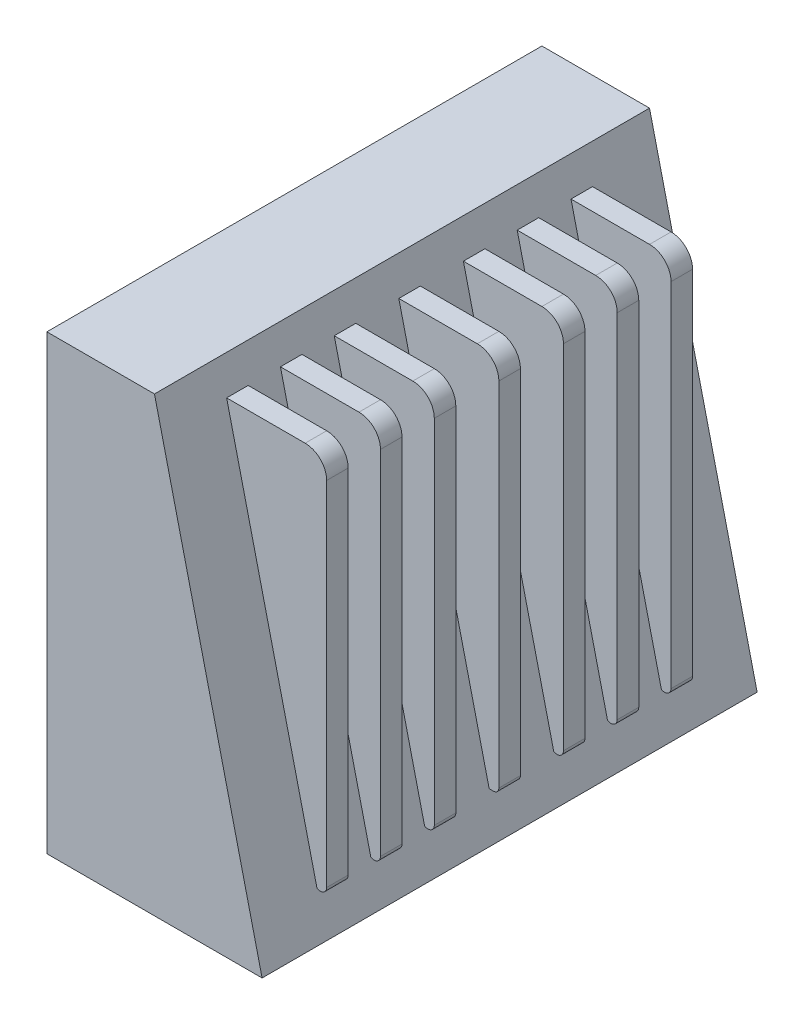
SolidWorks part; units mm, degrees
ref_plane "Alzado" through (0, 0, 0) normal (0, 0, 1) x (1, 0, 0)
ref_plane "Planta" through (0, 0, 0) normal (0, 1, 0) x (1, 0, 0)
ref_plane "Vista lateral" through (0, 0, 0) normal (1, 0, 0) x (0, 0, -1)
sketch "Croquis1" plane through (0, 0, 0) normal (0, 1, 0) x (1, 0, 0)
  line L1 (-10, -23) -> (10, -23)
  line L2 (-10, -23) -> (-10, 23)
  line L3 (-10, 23) -> (10, 23)
  line L4 (10, -23) -> (10, 23)
  line L5 (-10, -23) -> (10, 23) construction
  line L6 (-10, 23) -> (10, -23) construction
  point P0 (0, 0)
  dimension "D1" = 20
  dimension "D2" = 46
extrude "Saliente-Extruir1" add sketch "Croquis1" along normal blind 42
sketch "Croquis2" plane through (0, 0, 23) normal (0, 0, 1) x (1, 0, 0)
  line L0 (10, 0) -> (-0.1917, 42.8034)
  line L2 (-0.1917, 42.8034) -> (10, 42)
  line L3 (10, 42) -> (10, 0)
  dimension "D1" = 44
extrude "Cortar-Extruir1" cut sketch "Croquis2" against normal through all
sketch "Croquis3" plane through (0, 0, 0) normal (0, 0, 1) x (1, 0, 0)
  line L0 (10, 0) -> (10, 42) construction
  line L1 (-0.0004, 42) -> (10, 42) construction
  line L2 (9.0991, 3.7838) -> (9.5, 3.7838)
  line L3 (-0.0004, 42) -> (10, 0) construction
  line L4 (10, 4.2838) -> (10, 37.0371)
  line L5 (8, 39.0371) -> (0.7051, 39.0371)
  line L6 (0.7051, 39.0371) -> (9.0991, 3.7838)
  arc A0 (10, 37.0371) -> (8, 39.0371) centre (8, 37.0371) ccw
  arc A1 (9.5, 3.7838) -> (10, 4.2838) centre (9.5, 4.2838) ccw
  point P13 (10, 39.0371)
  point P16 (10, 3.7838)
  dimension "D1" = 2
  dimension "D2" = 0.5
extrude "Saliente-Extruir4" add sketch "Croquis3" along normal mid plane 2
ref_plane "Plano13" through (0, 0, 6) normal (0, 0, 1) x (1, 0, 0)
ref_plane "Plano14" through (0, 0, 11) normal (0, 0, 1) x (1, 0, 0)
ref_plane "Plano15" through (0, 0, 16) normal (0, 0, 1) x (1, 0, 0)
ref_plane "Plano16" through (0, 0, -6) normal (0, 0, -1) x (-1, 0, 0)
ref_plane "Plano17" through (0, 0, -11) normal (0, 0, -1) x (-1, 0, 0)
ref_plane "Plano18" through (0, 0, -16) normal (0, 0, -1) x (-1, 0, 0)
sketch "Croquis5" plane through (0, 0, 6) normal (0, 0, 1) x (1, 0, 0)
  line L0 (0.7051, 39.0371) -> (8, 39.0371)
  line L1 (10, 37.0371) -> (10, 4.2838)
  line L2 (9.0991, 3.7838) -> (0.7051, 39.0371)
  arc A0 (8, 39.0371) -> (10, 37.0371) centre (8, 37.0371) cw
  arc A1 (10, 37.0371) -> (8, 39.0371) centre (8, 37.0371) ccw construction
  arc A2 (10, 4.2838) -> (9.0991, 3.7838) centre (9.4108, 4.2838) cw
extrude "Saliente-Extruir5" add sketch "Croquis5" along normal mid plane 2
sketch "Croquis6" plane through (0, 0, 11) normal (0, 0, 1) x (1, 0, 0)
  line L0 (0.7051, 39.0371) -> (8, 39.0371)
  line L1 (10, 37.0371) -> (10, 4.2838)
  line L2 (9.0991, 3.7838) -> (0.7051, 39.0371)
  line L3 (8, 39.0371) -> (0.7051, 39.0371) construction
  line L4 (0.7051, 39.0371) -> (9.0991, 3.7838) construction
  line L5 (10, 4.2838) -> (10, 37.0371) construction
  arc A0 (8, 39.0371) -> (10, 37.0371) centre (8, 37.0371) cw
  arc A1 (10, 4.2838) -> (9.0991, 3.7838) centre (9.4108, 4.2838) cw
  arc A2 (9.0991, 3.7838) -> (10, 4.2838) centre (9.4108, 4.2838) ccw construction
extrude "Saliente-Extruir6" add sketch "Croquis6" along normal mid plane 2
sketch "Croquis7" plane through (0, 0, 16) normal (0, 0, 1) x (1, 0, 0)
  line L0 (0.7051, 39.0371) -> (8, 39.0371)
  line L1 (10, 37.0371) -> (10, 4.2838)
  line L2 (8.9072, 4.5896) -> (0.7051, 39.0371)
  line L3 (8, 39.0371) -> (0.7051, 39.0371) construction
  line L4 (0.7051, 39.0371) -> (9.0991, 3.7838) construction
  line L5 (10, 4.2838) -> (10, 37.0371) construction
  arc A0 (8, 39.0371) -> (10, 37.0371) centre (8, 37.0371) cw
  arc A1 (10, 4.2838) -> (8.9072, 4.5896) centre (9.4108, 4.2838) cw
  arc A2 (9.0991, 3.7838) -> (10, 4.2838) centre (9.4108, 4.2838) ccw construction
extrude "Saliente-Extruir7" add sketch "Croquis7" along normal mid plane 2
sketch "Croquis9" plane through (0, 0, -6) normal (0, 0, -1) x (-1, 0, 0)
  line L0 (-0.7051, 39.0371) -> (-8, 39.0371)
  line L1 (-10, 37.0371) -> (-10, 4.2838)
  line L2 (-9.0991, 3.7838) -> (-0.7051, 39.0371)
  arc A0 (-8, 39.0371) -> (-10, 37.0371) centre (-8, 37.0371) ccw
  arc A1 (-8, 39.0371) -> (-10, 37.0371) centre (-8, 37.0371) ccw construction
  arc A2 (-10, 4.2838) -> (-9.0991, 3.7838) centre (-9.4108, 4.2838) ccw
extrude "Saliente-Extruir8" add sketch "Croquis9" along normal mid plane 2
sketch "Croquis10" plane through (0, 0, -11) normal (0, 0, -1) x (-1, 0, 0)
  line L0 (-0.7051, 39.0371) -> (-8, 39.0371)
  line L1 (-10, 37.0371) -> (-10, 4.2838)
  line L2 (-8.9072, 4.5896) -> (-0.7051, 39.0371)
  line L3 (-0.7051, 39.0371) -> (-8, 39.0371) construction
  line L4 (-10, 37.0371) -> (-10, 4.2838) construction
  line L5 (0.0004, 42) -> (-10, 0) construction
  line L6 (-9.0991, 3.7838) -> (-8.9072, 4.5896)
  arc A0 (-8, 39.0371) -> (-10, 37.0371) centre (-8, 37.0371) ccw
  arc A3 (-10, 4.2838) -> (-9.0991, 3.7838) centre (-9.4108, 4.2838) ccw
extrude "Saliente-Extruir9" add sketch "Croquis10" along normal mid plane 2
sketch "Croquis11" plane through (0, 0, -16) normal (0, 0, -1) x (-1, 0, 0)
  line L0 (-0.7051, 39.0371) -> (-8, 39.0371)
  line L1 (-10, 37.0371) -> (-10, 4.2838)
  line L2 (-9.0991, 3.7838) -> (-0.7051, 39.0371)
  arc A0 (-8, 39.0371) -> (-10, 37.0371) centre (-8, 37.0371) ccw
  arc A1 (-10, 4.2838) -> (-9.0991, 3.7838) centre (-9.4108, 4.2838) ccw
extrude "Saliente-Extruir10" add sketch "Croquis11" along normal mid plane 2
